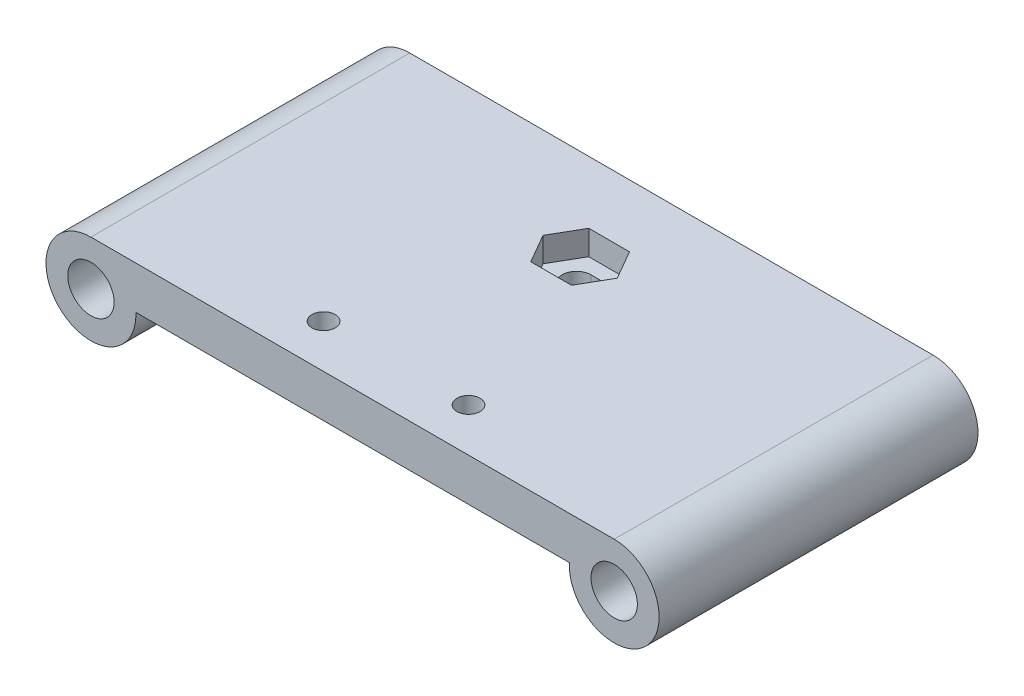
SolidWorks part; units mm, degrees
ref_plane "前视基准面" through (0, 0, 0) normal (0, 0, 1) x (1, 0, 0)
ref_plane "上视基准面" through (0, 0, 0) normal (0, 1, 0) x (1, 0, 0)
ref_plane "右视基准面" through (0, 0, 0) normal (1, 0, 0) x (0, 0, -1)
other "Configuration Table"
sketch "草图3" plane through (0, 0, 0) normal (0, 0, 1) x (1, 0, 0)
  line L0 (-18.05, -8.355) -> (18.05, -8.355)
  line L1 (-14.9539, -11.3) -> (14.9539, -11.3)
  line L2 (9.73, -11.3) -> (-9.73, -11.3) construction
  circle A0 centre (-18.05, -11.455) radius 1.6
  circle A1 centre (18.05, -11.455) radius 1.6
  circle A2 centre (-18.05, -11.455) radius 3.1
  circle A3 centre (18.05, -11.455) radius 3.1
  dimension "D1" = 1.5
  dimension "D2" = 3.2
extrude "凸台-拉伸1" add sketch "草图3" against normal blind 22 contours A3 A1 | A3 L0 A2 L1 | A2 A0
sketch "草图4" plane through (0, -11.3, 0) normal (0, -1, 0) x (1, 0, 0)
  line L0 (-0.25, -15.7) -> (0.25, -15.7) construction
  line L1 (-0.25, -14.7) -> (0.25, -14.7)
  line L2 (-0.25, -16.7) -> (0.25, -16.7)
  arc A0 (-0.25, -14.7) -> (-0.25, -16.7) centre (-0.25, -15.7) ccw
  arc A1 (0.25, -16.7) -> (0.25, -14.7) centre (0.25, -15.7) ccw
  point P2 (0, -15.7)
  dimension "D1" = 1
  dimension "D2" = 0.5
extrude "切除-拉伸1" cut sketch "草图4" against normal up to next
sketch "草图5" plane through (0, -8.355, 0) normal (0, 1, 0) x (1, 0, 0)
  line L1 (2.0594, 15.7) -> (0.9047, 17.7)
  line L2 (0.9047, 17.7) -> (-1.4047, 17.7)
  line L3 (-1.4047, 17.7) -> (-2.5594, 15.7)
  line L4 (-2.5594, 15.7) -> (-1.4047, 13.7)
  line L5 (-1.4047, 13.7) -> (0.9047, 13.7)
  line L6 (0.9047, 13.7) -> (2.0594, 15.7)
  line L7 (2.5594, 15.7) -> (1.4047, 17.7)
  line L8 (1.4047, 17.7) -> (-0.9047, 17.7)
  line L9 (-0.9047, 17.7) -> (-2.0594, 15.7)
  line L10 (-2.0594, 15.7) -> (-0.9047, 13.7)
  line L11 (-0.9047, 13.7) -> (1.4047, 13.7)
  line L12 (1.4047, 13.7) -> (2.5594, 15.7)
  circle A0 centre (-0.25, 15.7) radius 2 construction
  circle A1 centre (0.25, 15.7) radius 2 construction
  arc A4 (-0.25, 16.7) -> (-0.25, 14.7) centre (-0.25, 15.7) ccw construction
  arc A5 (0.25, 14.7) -> (0.25, 16.7) centre (0.25, 15.7) ccw construction
  line M13 (0.25, 14.7) -> (-0.25, 14.7)
  arc M14 (-0.25, 14.7) -> (-0.25, 16.7) centre (-0.25, 15.7) cw
  line M15 (-0.25, 16.7) -> (0.25, 16.7)
  arc M16 (0.25, 16.7) -> (0.25, 14.7) centre (0.25, 15.7) cw
  dimension "D1" = 4
extrude "切除-拉伸2" cut sketch "草图5" against normal blind 1.7 contours L10 L4 L5 M14 | L3 L4 M14 | L9 L2 L3 M14 | L10 L9 M14 | L9 L10 L6 L1 M14 M13 M16 M15 | L6 L1 M16 | L11 L12 L6 M16 | L12 L7 M16 | L7 L8 L1 M16 | L1 L2 M16 | L2 L9 M14 | L10 L5 M14 | L5 L6 M16
sketch "草图6" plane through (0, -8.355, 0) normal (0, 1, 0) x (1, 0, 0)
  circle A0 centre (-5, 3) radius 0.8
  circle A1 centre (5, 3) radius 0.8
  dimension "D1" = 1.6
extrude "切除-拉伸3" cut sketch "草图6" against normal up to next
sketch "草图7" plane through (0, -11.3, 0) normal (0, -1, 0) x (1, 0, 0)
  circle A0 centre (5, -3) radius 1.4
  circle A1 centre (-5, -3) radius 1.4
  dimension "D1" = 2.8
extrude "切除-拉伸4" cut sketch "草图7" against normal blind 0.5
